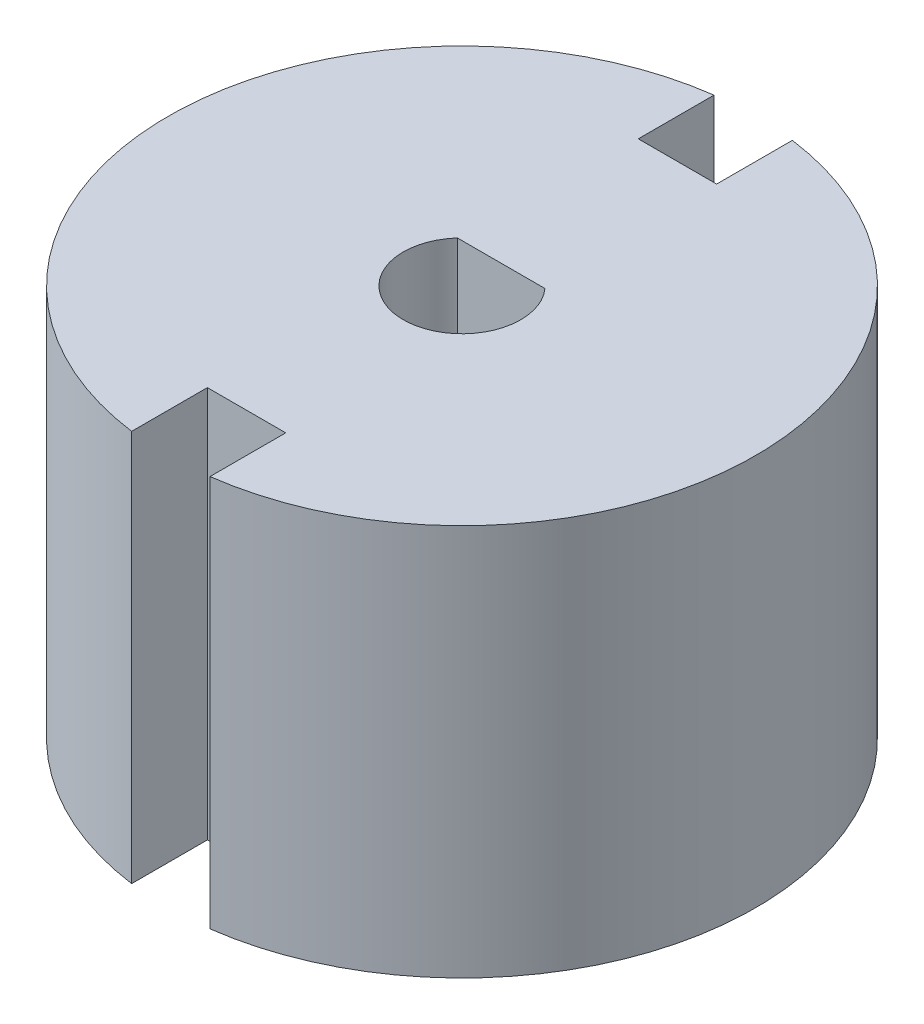
SolidWorks part; units mm, degrees
ref_plane "Front" through (0, 0, 0) normal (0, 0, 1) x (1, 0, 0)
ref_plane "Top" through (0, 0, 0) normal (0, 1, 0) x (1, 0, 0)
ref_plane "Right" through (0, 0, 0) normal (1, 0, 0) x (0, 0, -1)
sketch "Эскиз1" plane through (0, 0, 0) normal (0, 1, 0) x (1, 0, 0)
  line L0 (-7.5, 0) -> (7.5, 0) construction
  line L1 (0, -7.5) -> (0, 7.5) construction
  line L2 (-1, 8.5) -> (1, 8.5)
  line L3 (-1, 8.5) -> (-1, 5.5)
  line L4 (-1, 5.5) -> (1, 5.5)
  line L5 (1, 8.5) -> (1, 5.5)
  line L6 (-1, -5.5) -> (1, -5.5)
  line L7 (-1, -5.5) -> (-1, -8.5)
  line L8 (-1, -8.5) -> (1, -8.5)
  line L9 (1, -5.5) -> (1, -8.5)
  line L10 (-1.118, 1) -> (1.118, 1)
  circle A0 centre (0, 0) radius 7.5
  circle A1 centre (0, 0) radius 1.5
  dimension "D1" = 15
  dimension "D5" = 3
  dimension "D2" = 3
  dimension "D3" = 2
  dimension "D4" = 2
  dimension "D6" = 1
extrude "Бобышка-Вытянуть1" add sketch "Эскиз1" along normal blind 10 contours L9 A0 L5 L4 L3 L7 L6 A1 | L10 A1
